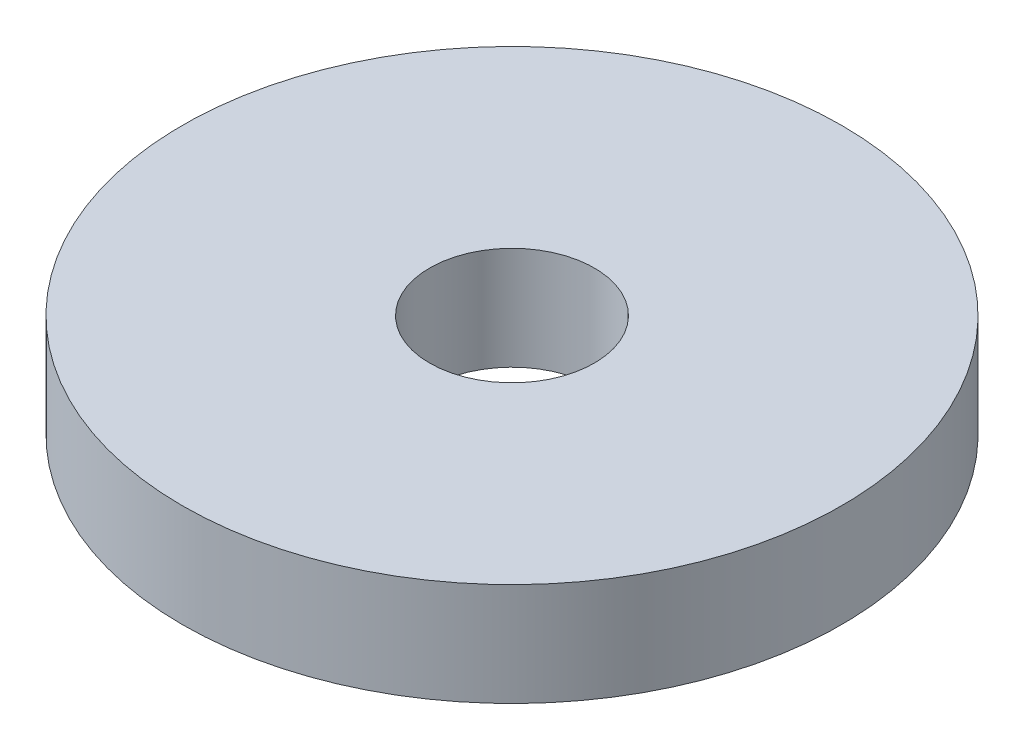
SolidWorks part; units mm, degrees
ref_plane "Front Plane" through (0, 0, 0) normal (0, 0, 1) x (1, 0, 0)
ref_plane "Top Plane" through (0, 0, 0) normal (0, 1, 0) x (1, 0, 0)
ref_plane "Right Plane" through (0, 0, 0) normal (1, 0, 0) x (0, 0, -1)
sketch "Sketch1" plane through (0, 0, 0) normal (0, 1, 0) x (1, 0, 0)
  circle A0 centre (0, 0) radius 16
  arc A6 (-15.3109, -4.6451) -> (15.2788, -4.7496) centre (0, 0) ccw construction
  circle A7 centre (0, 0) radius 4
  dimension "D1" = 8
extrude "Boss-Extrude1" add sketch "Sketch1" along normal blind 5
